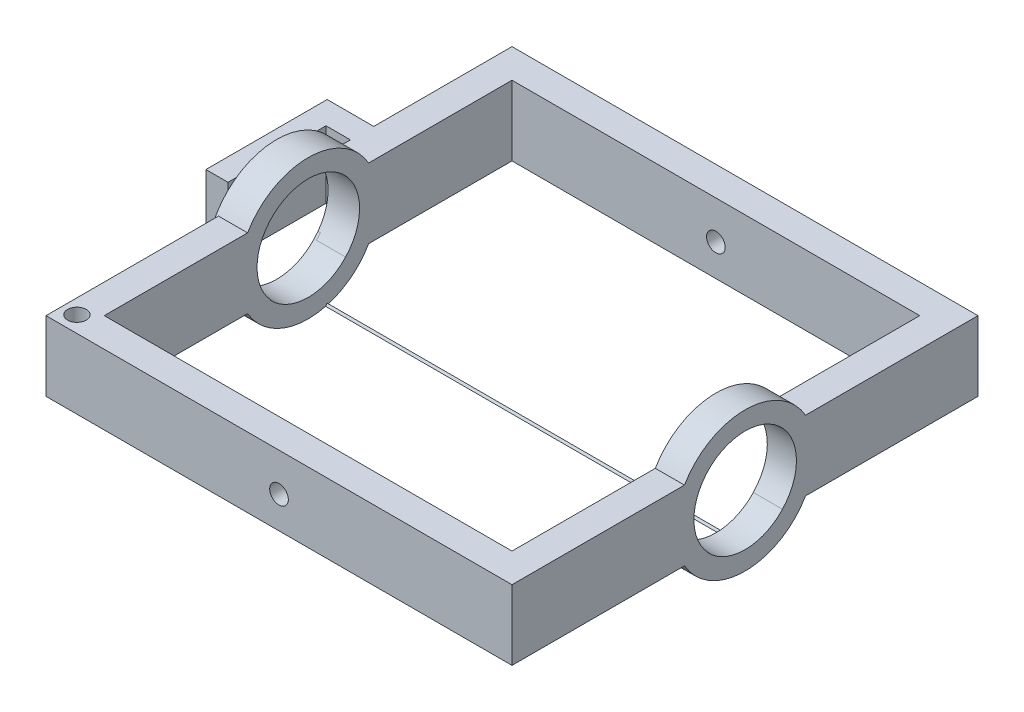
SolidWorks part; units mm, degrees
ref_plane "Front Plane" through (0, 0, 0) normal (0, 0, 1) x (1, 0, 0)
ref_plane "Top Plane" through (0, 0, 0) normal (0, 1, 0) x (1, 0, 0)
ref_plane "Right Plane" through (0, 0, 0) normal (1, 0, 0) x (0, 0, -1)
sketch "Sketch1" plane through (0, 0, 0) normal (0, 1, 0) x (1, 0, 0)
  line L1 (-100, 100) -> (100, 100)
  line L2 (-100, 100) -> (-100, -100)
  line L3 (-100, -100) -> (100, -100)
  line L4 (100, 100) -> (100, -100)
  line L5 (-100, 100) -> (100, -100) construction
  line L6 (-100, -100) -> (100, 100) construction
  point P0 (0, 0)
extrude "Boss-Extrude1" add sketch "Sketch1" along normal blind 30
sketch "Sketch4" plane through (0, 30, 0) normal (0, 1, 0) x (1, 0, 0)
  line L1 (-87.5, -87.5) -> (87.5, -87.5)
  line L2 (-87.5, -87.5) -> (-87.5, 87.5)
  line L3 (-87.5, 87.5) -> (87.5, 87.5)
  line L4 (87.5, -87.5) -> (87.5, 87.5)
  line L5 (-87.5, -87.5) -> (87.5, 87.5) construction
  line L6 (-87.5, 87.5) -> (87.5, -87.5) construction
  point P0 (0, 0)
extrude "Cut-Extrude1" cut sketch "Sketch4" against normal blind 30
sketch "Sketch7" plane through (-100, 0, 0) normal (-1, 0, 0) x (0, 0, 1)
  circle A0 centre (0, 15) radius 4
extrude "Cut-Extrude2" cut sketch "Sketch7" against normal blind 210
sketch "Sketch10" plane through (-100, 0, 0) normal (-1, 0, 0) x (0, 0, 1)
  line L0 (-8.6266, 30) -> (-8.6266, 0)
  line L1 (-100, 30) -> (100, 30) construction
  line L2 (-100, 0) -> (100, 0) construction
  line L3 (-8.6266, 0) -> (-14.6668, 0)
  line L4 (-14.6668, 0) -> (-14.6668, 30)
  line L5 (-14.6668, 30) -> (-8.6266, 30)
extrude "Boss-Extrude2" add sketch "Sketch10" along normal blind 20
sketch "Sketch11" plane through (0, 0, -8.6266) normal (0, 0, 1) x (1, 0, 0)
  line L0 (-120, 0) -> (-120, 30)
  line L1 (-120, 30) -> (-110, 30)
  line L2 (-120, 30) -> (-100, 30) construction
  line L3 (-110, 30) -> (-110, 0)
  line L4 (-120, 0) -> (-100, 0) construction
  line L5 (-110, 0) -> (-120, 0)
extrude "Boss-Extrude3" add sketch "Sketch11" along normal blind 20
sketch "Sketch12" plane through (100, 0, 0) normal (1, 0, 0) x (0, 0, -1)
  circle A0 centre (0, 15) radius 4
extrude "Cut-Extrude3" cut sketch "Sketch12" against normal blind 231
sketch "Sketch13" plane through (0, 30, 0) normal (0, 1, 0) x (1, 0, 0)
  circle A0 centre (-93.6945, -93.0455) radius 4
extrude "Cut-Extrude5" cut sketch "Sketch13" against normal blind 231
sketch "Sketch14" plane through (0, 0, 100) normal (0, 0, 1) x (1, 0, 0)
  circle A0 centre (0, 13.6147) radius 4
extrude "Cut-Extrude6" cut sketch "Sketch14" against normal blind 250.5
sketch "Sketch15" plane through (100, 0, 0) normal (1, 0, 0) x (0, 0, -1)
  circle A0 centre (0, 15) radius 30
  circle A1 centre (0, 15) radius 22
extrude "Boss-Extrude5" add sketch "Sketch15" against normal blind 201
sketch "Sketch17" plane through (100, 0, 0) normal (1, 0, 0) x (0, 0, -1)
  circle A0 centre (0.0744, 15.1008) radius 22
extrude "Cut-Extrude7" cut sketch "Sketch17" against normal blind 201
sketch "Sketch18" plane through (87.5, 0, 0) normal (-1, 0, 0) x (0, 0, 1)
  line L1 (-87.5, 0) -> (87.5, 0)
  line L2 (-87.5, 0) -> (-87.5, 30)
  line L3 (-87.5, 30) -> (87.5, 30)
  line L4 (87.5, 0) -> (87.5, 30)
sketch "Sketch21" plane through (0, 0, -14.6668) normal (0, 0, -1) x (-1, 0, 0)
  line L0 (120, 30) -> (120, 0) construction
  line L1 (120, 1.1441) -> (110.5, 1.1441)
  line L2 (120, 1.1441) -> (120, 30)
  line L3 (120, 30) -> (110.5, 30)
  line L4 (110.5, 1.1441) -> (110.5, 30)
  line L5 (120, 30) -> (101, 30) construction
extrude "Boss-Extrude6" add sketch "Sketch21" along normal blind 26
sketch "Sketch22" plane through (0, 30, 0) normal (0, 1, 0) x (1, 0, 0)
  line L1 (-110.5, 14.6668) -> (-101, 14.6668)
  line L2 (-110.5, 14.6668) -> (-110.5, 8.6266)
  line L3 (-110.5, 8.6266) -> (-101, 8.6266)
  line L4 (-101, 14.6668) -> (-101, 8.6266)
extrude "Cut-Extrude10" cut sketch "Sketch22" against normal blind 49
sketch "Sketch23" plane through (-110.5, 0, 0) normal (1, 0, 0) x (0, 0, -1)
  line L0 (40.6668, 1.1441) -> (14.6668, 1.1441) construction
  line L1 (40.6668, 30) -> (30.6579, 30)
  line L2 (40.6668, 30) -> (40.6668, 1.1441)
  line L3 (40.6668, 1.1441) -> (30.6579, 1.1441)
  line L4 (30.6579, 30) -> (30.6579, 1.1441)
extrude "Boss-Extrude7" add sketch "Sketch23" along normal blind 21
sketch "Sketch24" plane through (0, 0, -14.6668) normal (0, 0, -1) x (-1, 0, 0)
  line L1 (120, 0) -> (110.5, 0)
  line L2 (120, 0) -> (120, 1.1441)
  line L3 (120, 1.1441) -> (110.5, 1.1441)
  line L4 (110.5, 0) -> (110.5, 1.1441)
extrude "Cut-Extrude11" cut sketch "Sketch24" against normal blind 27
sketch "Sketch26" plane through (0, 0, 0) normal (0, -1, 0) x (1, 0, 0)
  line L1 (-110.5, -8.6266) -> (-109.9986, -8.6266)
  line L2 (-110.5, -8.6266) -> (-110.5, 12.267)
  line L3 (-110.5, 12.267) -> (-109.9986, 12.267)
  line L4 (-109.9986, -8.6266) -> (-109.9986, 12.267)
extrude "Cut-Extrude12" cut sketch "Sketch26" against normal blind 35
sketch "Sketch27" plane through (-87.5, 0, 0) normal (1, 0, 0) x (0, 0, -1)
  circle A0 centre (-31.9164, 15.3761) radius 49.1928
extrude "Cut-Extrude13" cut sketch "Sketch27" along normal blind 175
sketch "Sketch28" plane through (-87.5, 0, 0) normal (1, 0, 0) x (0, 0, -1)
  circle A0 centre (37.7624, 15.4944) radius 41.209
extrude "Cut-Extrude14" cut sketch "Sketch28" along normal blind 175
sketch "Sketch29" plane through (100, 0, 0) normal (1, 0, 0) x (0, 0, -1)
  circle A0 centre (0, 15) radius 30
sketch "Sketch30" plane through (87.5, 0, 0) normal (-1, 0, 0) x (0, 0, 1)
  circle A0 centre (-13.582, -10.1635) radius 19.2473
